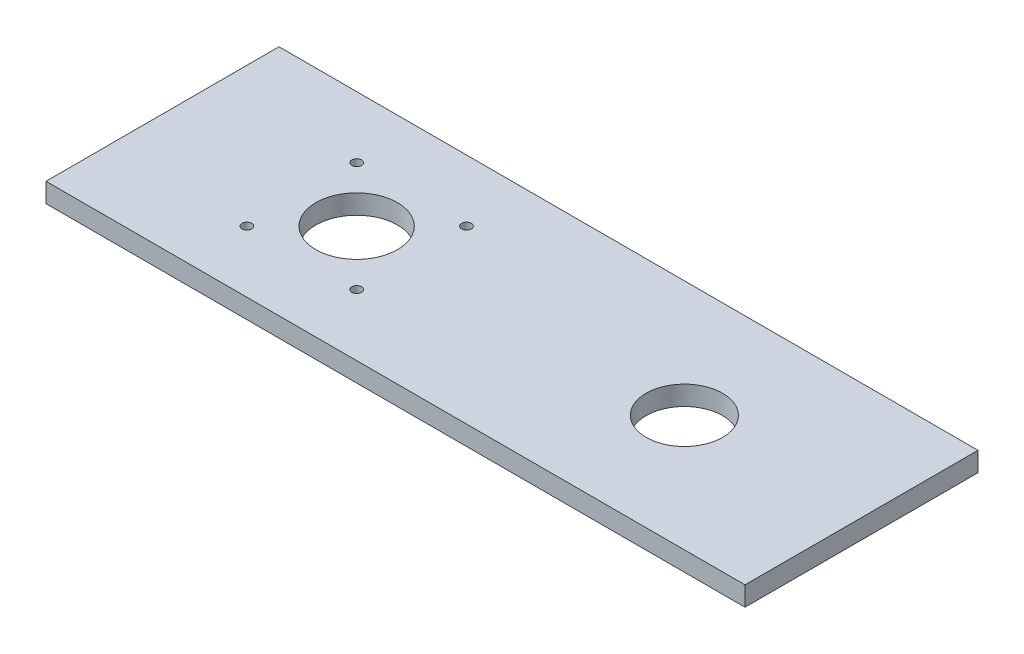
SolidWorks part; units mm, degrees
ref_plane "Front Plane" through (0, 0, 0) normal (0, 0, 1) x (1, 0, 0)
ref_plane "Top Plane" through (0, 0, 0) normal (0, 1, 0) x (1, 0, 0)
ref_plane "Right Plane" through (0, 0, 0) normal (1, 0, 0) x (0, 0, -1)
sketch "Sketch1" plane through (0, 0, 0) normal (0, 1, 0) x (1, 0, 0)
  line L0 (-50, 30) -> (130, 30)
  line L2 (-50, 30) -> (-50, -30)
  line L4 (130, 30) -> (130, -30)
  line L5 (130, -30) -> (-50, -30)
  circle A0 centre (0, 0) radius 10.5
  circle A3 centre (84.3856, 0) radius 9.8483
  point P0 (0, 0)
  dimension "D1" = 21
  dimension "D2" = 180
  dimension "D3" = 60
  dimension "D4" = 50
extrude "Boss-Extrude1" add sketch "Sketch1" along normal blind 5
hole_wizard "M3x0.5 Tapped Hole1" positions "Sketch3" profile "Sketch4" tap size "M3x0.5" standard "ANSI Metric" end condition through all
sketch "Sketch3" plane through (0, 5, 0) normal (0, 1, 0) x (1, 0, 0)
  line L4 (-14.1421, 14.1421) -> (0, 0) construction
  line L5 (0, 0) -> (0, 30) construction
  line L6 (130, 30) -> (-50, 30) construction
  point P0 (-14.1421, 14.1421)
  point P36 (14.1421, 14.1421)
  point P37 (14.1421, -14.1421)
  point P38 (-14.1421, -14.1421)
  point P39 (0, 0)
  dimension "D1" = 4
  dimension "D2" = 45
  dimension "D3" = 20
sketch "Sketch4" plane through (-14.1421, 5, -14.1421) normal (1, 0, 0) x (0, 0, 1)
  line L0 (0, 0) -> (0, 5)
  line L1 (0, 5) -> (1.25, 5)
  line L2 (1.25, 5) -> (1.25, 0)
  line L5 (1.25, 0) -> (0, 0)
  line L11 (0, -6.35) -> (0, 107.95) construction
  dimension "Thru Tap Drill Dia." = 2.5
  dimension "Thru Tap Drill Depth" = 5
cosmetic thread "Hole Thread1"
cosmetic thread "Hole Thread2"
cosmetic thread "Hole Thread3"
cosmetic thread "Hole Thread4"
